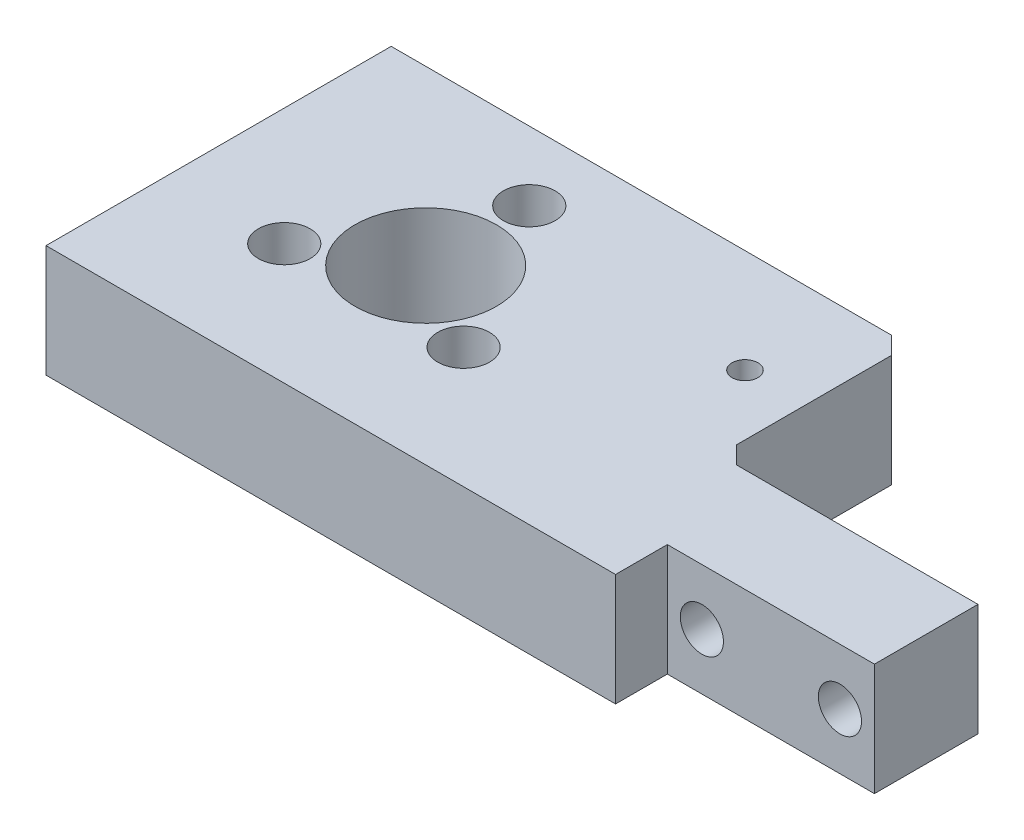
SolidWorks part; units mm, degrees
ref_plane "前视基准面" through (0, 0, 0) normal (0, 0, 1) x (1, 0, 0)
ref_plane "上视基准面" through (0, 0, 0) normal (0, 1, 0) x (1, 0, 0)
ref_plane "右视基准面" through (0, 0, 0) normal (1, 0, 0) x (0, 0, -1)
sketch "草图1" plane through (0, 0, 0) normal (0, 1, 0) x (1, 0, 0)
  line L0 (-12, 0) -> (35, 0) construction
  line L1 (-12, -10) -> (-12, 10)
  line L2 (-12, 10) -> (35, 10)
  line L3 (35, 10) -> (35, -10)
  line L4 (-12, -10) -> (35, -10)
  circle A0 centre (0, 0) radius 10 construction
  circle A1 centre (0, 0) radius 6 construction
  circle A2 centre (0, 6) radius 1.5
  circle A3 centre (5.1962, -3) radius 1.5
  circle A4 centre (-5.1962, -3) radius 1.5
  circle A5 centre (0, 0) radius 4.1
  point P12 (0, 0)
  dimension "D1" = 20
  dimension "D2" = 12
  dimension "D3" = 3
  dimension "D5" = 8.2
  dimension "D6" = 12
  dimension "D7" = 35
  dimension "D8" = 20
  dimension "D4" = 3
extrude "凸台-拉伸1" add sketch "草图1" along normal blind 6.5
sketch "草图2" plane through (0, 6.5, 0) normal (0, 1, 0) x (1, 0, 0)
  line L0 (-12, -10) -> (35, -10) construction
  line L1 (21, -10) -> (33, -10)
  line L2 (21, -10) -> (21, -7)
  line L3 (21, -7) -> (33, -7)
  line L4 (33, -10) -> (33, -7)
  line L5 (-12, 10) -> (-12, -10) construction
  line L7 (35, 10) -> (18, 10)
  line L8 (35, 10) -> (35, -1)
  line L9 (35, -1) -> (18, -1)
  line L10 (18, 10) -> (18, -1)
  dimension "D1" = 12
  dimension "D2" = 3
  dimension "D3" = 33
  dimension "D4" = 6
  dimension "D5" = 17
extrude "切除-拉伸1" cut sketch "草图2" against normal through all
sketch "草图3" plane through (0, 0, 7) normal (0, 0, 1) x (1, 0, 0)
  line L0 (21, 3.25) -> (35, 3.25) construction
  line L1 (21, 0) -> (21, 6.5) construction
  line L2 (35, 0) -> (35, 6.5) construction
  line L3 (27, 6.5) -> (27, 0) construction
  line L4 (33, 6.5) -> (21, 6.5) construction
  line L5 (33, 0) -> (21, 0) construction
  circle A0 centre (23, 3.25) radius 1.25
  circle A1 centre (31, 3.25) radius 1.25
  dimension "D1" = 2.5
  dimension "D2" = 8
extrude "切除-拉伸2" cut sketch "草图3" against normal through all
sketch "草图4" plane through (0, 6.5, 0) normal (0, 1, 0) x (1, 0, 0)
  line L0 (35, -10) -> (35, -1) construction
  line L1 (-12, 10) -> (35, 10) construction
  line L2 (-12, 10) -> (-12, -10.4025) construction
  line L3 (-12, -10.4025) -> (35, -10.4025) construction
  line L4 (35, 10) -> (35, -10.4025) construction
  line L5 (-12, -0.2012) -> (35, -0.2012) construction
  line L6 (11.5, 10) -> (11.5, -10.4025) construction
  line L7 (14.5, 10) -> (14.5, -10.4025) construction
  circle A1 centre (14.5, 3.9988) radius 0.75
  dimension "D2" = 1.5
  dimension "D3" = 4.2
  dimension "D1" = 3
extrude "切除-拉伸3" cut sketch "草图4" against normal through all
chamfer "倒角1" distance 1 angle 45 2 edges at (18, 3.25, 1) (18, 3.25, -10)
sketch "草图5" plane through (0, 6.5, 0) normal (0, 1, 0) x (1, 0, 0)
  line L1 (35, -1) -> (33, -1)
  line L2 (35, -1) -> (35, -10)
  line L3 (35, -10) -> (33, -10)
  line L4 (33, -1) -> (33, -10)
extrude "切除-拉伸4" cut sketch "草图5" against normal through all
